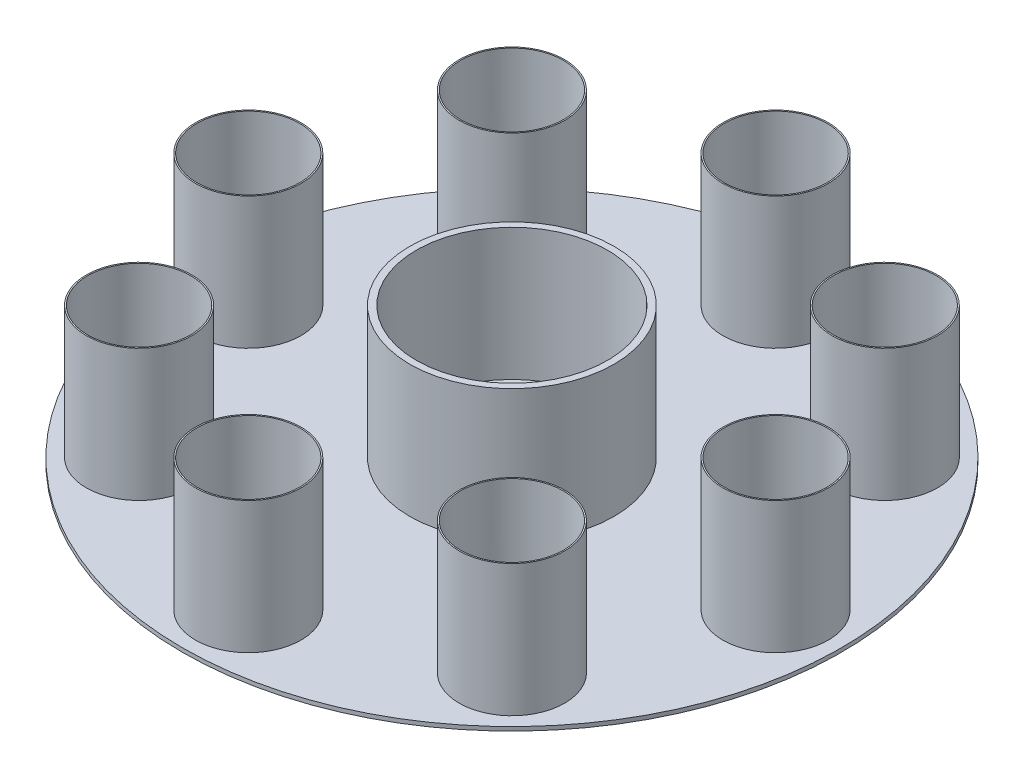
SolidWorks part; units mm, degrees
ref_plane "Front Plane" through (0, 0, 0) normal (0, 0, 1) x (1, 0, 0)
ref_plane "Top Plane" through (0, 0, 0) normal (0, 1, 0) x (1, 0, 0)
ref_plane "Right Plane" through (0, 0, 0) normal (1, 0, 0) x (0, 0, -1)
sketch "Sketch1" plane through (0, 0, 0) normal (0, 1, 0) x (1, 0, 0)
  line L0 (0, 0) -> (0, 250) construction
  line L1 (0, 0) -> (0, -250) construction
  line L2 (0, 0) -> (250, 0) construction
  line L3 (0, 0) -> (-250, 0) construction
  line L4 (0, 0) -> (176.7767, 176.7767) construction
  line L5 (0, 0) -> (176.7767, -176.7767) construction
  circle A0 centre (0, 0) radius 250
  circle A1 centre (141.4214, 141.4214) radius 39
  circle A2 centre (-141.4214, 141.4214) radius 39
  circle A3 centre (-141.4214, -141.4214) radius 39
  circle A4 centre (141.4214, -141.4214) radius 39
  circle A5 centre (0, 200) radius 39
  circle A6 centre (200, 0) radius 39
  circle A7 centre (0, -200) radius 39
  circle A8 centre (-200, 0) radius 39
  point P19 (0, 0)
  point P20 (0, 0)
  dimension "D1" = 500
  dimension "D3" = 78
  dimension "D5" = 78
  dimension "D7" = 78
  dimension "D2" = 45
  dimension "D4" = 200
  dimension "D6" = 200
extrude "Boss-Extrude1" add sketch "Sketch1" along normal blind 3
sketch "Sketch2" plane through (0, 3, 0) normal (0, 1, 0) x (1, 0, 0)
  circle A0 centre (0, 200) radius 40
  circle A1 centre (0, 200) radius 39
  circle A2 centre (141.4214, 141.4214) radius 39
  circle A3 centre (141.4214, 141.4214) radius 40
  circle A4 centre (200, 0) radius 39
  circle A5 centre (200, 0) radius 40
  circle A6 centre (141.4214, -141.4214) radius 39
  circle A7 centre (141.4214, -141.4214) radius 40
  circle A8 centre (0, -200) radius 39
  circle A9 centre (0, -200) radius 40
  circle A10 centre (-141.4214, -141.4214) radius 39
  circle A11 centre (-141.4214, -141.4214) radius 40
  circle A12 centre (-200, 0) radius 39
  circle A13 centre (-200, 0) radius 40
  circle A14 centre (-141.4214, 141.4214) radius 39
  circle A15 centre (-141.4214, 141.4214) radius 40
extrude "Boss-Extrude2" add sketch "Sketch2" along normal blind 100
sketch "Sketch3" plane through (0, 3, 0) normal (0, 1, 0) x (1, 0, 0)
  circle A0 centre (0, 0) radius 72.5
  circle A1 centre (0, 0) radius 77.5
  dimension "D1" = 145
  dimension "D2" = 155
extrude "Boss-Extrude3" add sketch "Sketch3" along normal blind 100
